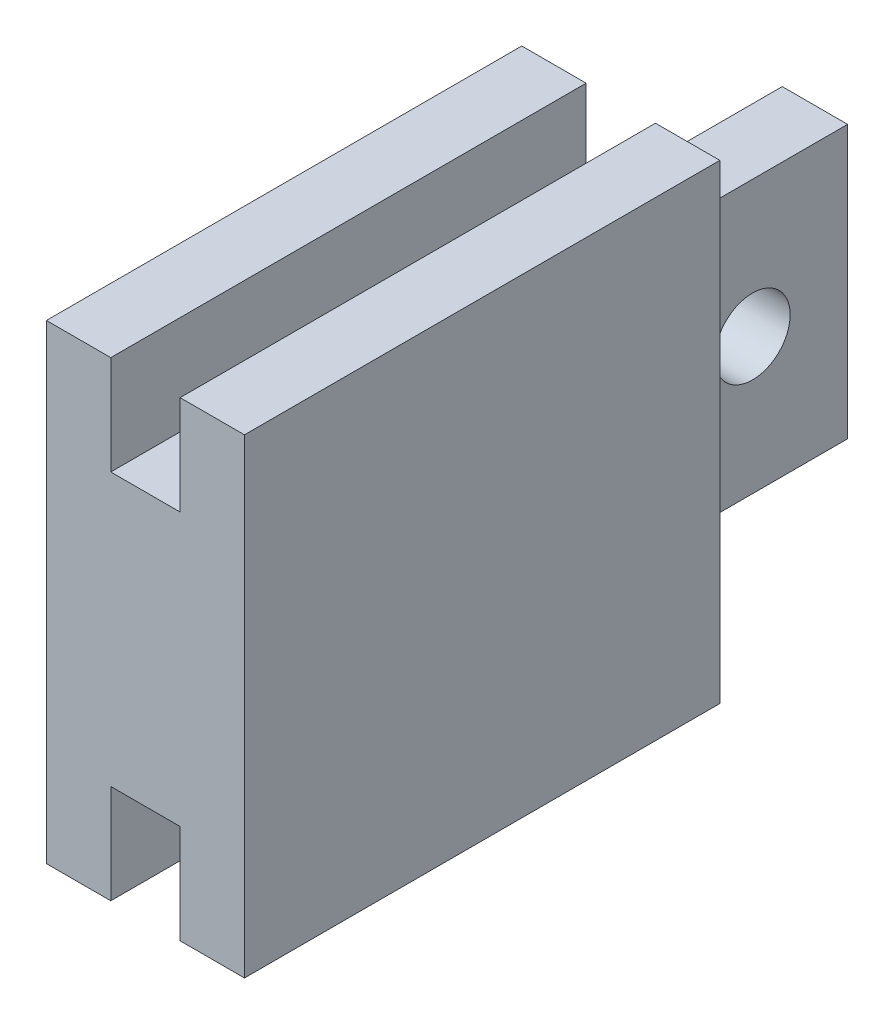
SolidWorks part; units mm, degrees
ref_plane "Front Plane" through (0, 0, 0) normal (1, 0, 0) x (0, 1, 0)
ref_plane "Top Plane" through (0, 0, 0) normal (0, 0, 1) x (0, 1, 0)
ref_plane "Right Plane" through (0, 0, 0) normal (0, 1, 0) x (-1, 0, 0)
sketch "Sketch1" plane through (0, 0, 0) normal (1, 0, 0) x (0, 1, 0)
  line L1 (0, 0) -> (23.75, 0)
  line L2 (0, 0) -> (0, 24)
  line L3 (0, 24) -> (23.75, 24)
  line L4 (23.75, 0) -> (23.75, 24)
  dimension "D1" = 23.75
  dimension "D2" = 24
extrude "Boss-Extrude1" add sketch "Sketch1" against normal blind 10
sketch "Sketch2" plane through (0, 0, 0) normal (0, -1, 0) x (1, 0, 0)
  line L1 (-10, 0) -> (-6.65, 0)
  line L2 (-10, 0) -> (-10, -9.8)
  line L3 (-10, -9.8) -> (-6.65, -9.8)
  line L4 (-6.65, 0) -> (-6.65, -9.8)
  line L5 (0, 0) -> (-3.35, 0)
  line L6 (0, 0) -> (0, -9.8)
  line L7 (0, -9.8) -> (-3.35, -9.8)
  line L8 (-3.35, 0) -> (-3.35, -9.8)
  line L9 (-6.65, -9.8) -> (-3.35, -9.8)
  line L10 (-6.65, -9.8) -> (-6.65, 0)
  line L11 (-6.65, 0) -> (-3.35, 0)
  line L12 (-3.35, -9.8) -> (-3.35, 0)
  line M12 (-10, 0) -> (0, 0)
  dimension "D1" = 9.8
  dimension "D2" = 3.35
  dimension "D3" = 3.35
extrude "Boss-Extrude2" add sketch "Sketch2" against normal through all contours L4 L9 L8 M12
sketch "Sketch3" plane through (0, 0, 0) normal (0, -1, 0) x (1, 0, 0)
  line L0 (-3.35, 20.65) -> (-3.35, 3.35)
  line L1 (0, 24) -> (-10, 24)
  line L2 (0, 24) -> (0, 0)
  line L3 (0, 0) -> (-10, 0)
  line L4 (-10, 24) -> (-10, 0)
  line L5 (-3.35, 3.35) -> (-6.65, 3.35)
  line L6 (-6.65, 20.65) -> (-6.65, 3.35)
  line L7 (-3.35, 20.65) -> (-6.65, 20.65)
  line L9 (-6.65, 20.65) -> (-3.35, 20.65)
  line L10 (-6.65, 20.65) -> (-6.65, 24)
  line L11 (-6.65, 24) -> (-3.35, 24)
  line L12 (-3.35, 20.65) -> (-3.35, 24)
  dimension "D1" = 3.35
extrude "Boss-Extrude3" [suppressed] add sketch "Sketch3" along normal blind 4.9 contours L0 L7 L6 L5 | L10 L9 L12 L11
sketch "Sketch4" plane through (-6.65, 0, 0) normal (-1, 0, 0) x (0, -1, 0)
  line L0 (0, 0) -> (-23.75, 0) construction
  line L1 (-11.875, 0) -> (-23.75, 0)
  line L2 (-11.875, 0) -> (-11.875, -5)
  line L3 (-11.875, -5) -> (-23.75, -5)
  line L4 (-23.75, 0) -> (-23.75, -5)
  circle A0 centre (-11.875, -5) radius 1.9
  dimension "D2" = 3.8
  dimension "D1" = 5
extrude "Cut-Extrude1" cut sketch "Sketch4" against normal up to next contours A0
sketch "Sketch5" plane through (0, 23.75, 0) normal (0, 1, 0) x (-1, 0, 0)
  line L0 (3.25, 20.75) -> (3.25, 3.25)
  line L1 (0, 24) -> (10, 24)
  line L2 (0, 24) -> (0, 0)
  line L3 (0, 0) -> (10, 0)
  line L4 (10, 24) -> (10, 0)
  line L5 (3.25, 3.25) -> (6.75, 3.25)
  line L6 (6.75, 20.75) -> (6.75, 3.25)
  line L7 (3.25, 20.75) -> (6.75, 20.75)
  line L9 (3.25, 20.75) -> (6.75, 20.75)
  line L10 (3.25, 20.75) -> (3.25, 24)
  line L11 (3.25, 24) -> (6.75, 24)
  line L12 (6.75, 20.75) -> (6.75, 24)
  line L13 (3.25, 3.25) -> (6.75, 3.25)
  line L14 (3.25, 3.25) -> (3.25, -9.8)
  line L15 (3.25, -9.8) -> (6.75, -9.8)
  line L16 (6.75, 3.25) -> (6.75, -9.8)
  line M11 (3.35, 0) -> (3.35, -9.8)
  line M12 (3.35, -9.8) -> (6.65, -9.8)
  line M13 (6.65, -9.8) -> (6.65, 0)
  line M14 (6.65, 0) -> (10, 0)
  dimension "D1" = 3.25
extrude "Cut-Extrude2" cut sketch "Sketch5" against normal blind 5 contours L7 L12 L1 L10 | L7 L0 L5 L6 | L16 L5 L14 L3 M14 | L3 M11 M12 M13
ref_plane "Plane1" through (0, 11.875, 0) normal (0, 1, 0) x (1, 0, 0)
mirror "Mirror1" about plane through (0, 11.875, 0) normal (0, 1, 0) of "Cut-Extrude2"
equation "\"whitekey_cutout_length\"= 101.5"
equation "\"key_mount_recess_length\"=50"
equation "\"key_mount_recess_height\"=12.5"
equation "\"key_mount_recess_depth\"=1.5"
equation "\"wall_thickness\"=10"
equation "\"guide_brace_height\"=20"
equation "\"guide_brace_thickness\"=2"
equation "\"dowel_recess_depth\"=10"
equation "\"dowel_recess_offset\"=3.25"
equation "\"base_mount_height\"=40"
equation "\"base_rear_length\"=80"
equation "\"base_front_length\"=111.5"
equation "\"screw_hole_wall_offset\"=7.25"
equation "\"screw_hole_edge_inset\"=\"dowel_recess_depth\"/2"
equation "\"screw_hole_diameter\"=3.8"
equation "\"screw_head_hole_diameter\"=6.7"
equation "\"screw_nut_hole_side_len\"=3.5"
equation "\"screw_shaft_diameter\"=3.5"
equation "\"switch_board_width\"=30"
equation "\"switch_board_wall_offset\"=11.5"
equation "\"heatset_insert_hole_diameter\"=4.8"
equation "\"heatset_insert_hole_depth\"=3.8"
equation "\"D1@Boss-Extrude1\"=\"wall_thickness\""
equation "\"D2@Sketch2\"=\"dowel_recess_offset\"+\"dowel_insert_tolerance\""
equation "\"D3@Sketch2\"=\"dowel_recess_offset\"+\"dowel_insert_tolerance\""
equation "\"D1@Boss-Extrude3\"=\"front_rear_panel_recess_depth\"-\"dowel_insert_tolerance\""
equation "\"D1@Sketch3\"=\"dowel_recess_offset\"+\"dowel_insert_tolerance\""
equation "\"D1@Sketch2\"=\"dowel_recess_depth\"-\"dowel_insert_tolerance\"*2"
equation "\"D1@Sketch4\"=\"screw_hole_edge_inset\""
equation "\"D2@Sketch4\"=\"screw_hole_diameter\""
equation "\"D1@Sketch5\"=\"dowel_recess_offset\""
equation "\"D1@Cut-Extrude2\"=\"front_rear_panel_recess_depth\""
equation "\"screw_nut_recess_offset\"=0.35"
equation "\"screw_head_and_nut_recess_depth\"=2.5"
equation "\"front_rear_panel_width\"=23.75"
equation "\"rod_length_adj\"=0.5"
equation "\"rod_insert_length\"=2.8"
equation "\"D1@Sketch1\"=\"front_rear_panel_width\""
equation "\"switch_board_thickness\"=1.6"
equation "\"front_panel_height\"=24"
equation "\"rod_diameter\"=5"
equation "\"rod_head_diameter\"=8"
equation "\"switch_black_key_mount_height\"=8"
equation "\"switch_white_key_mount_height\"=3"
equation "\"D2@Sketch1\"=\"front_panel_height\""
equation "\"dowel_insert_tolerance\"=0.1"
equation "\"front_rear_panel_recess_depth\"=5"
